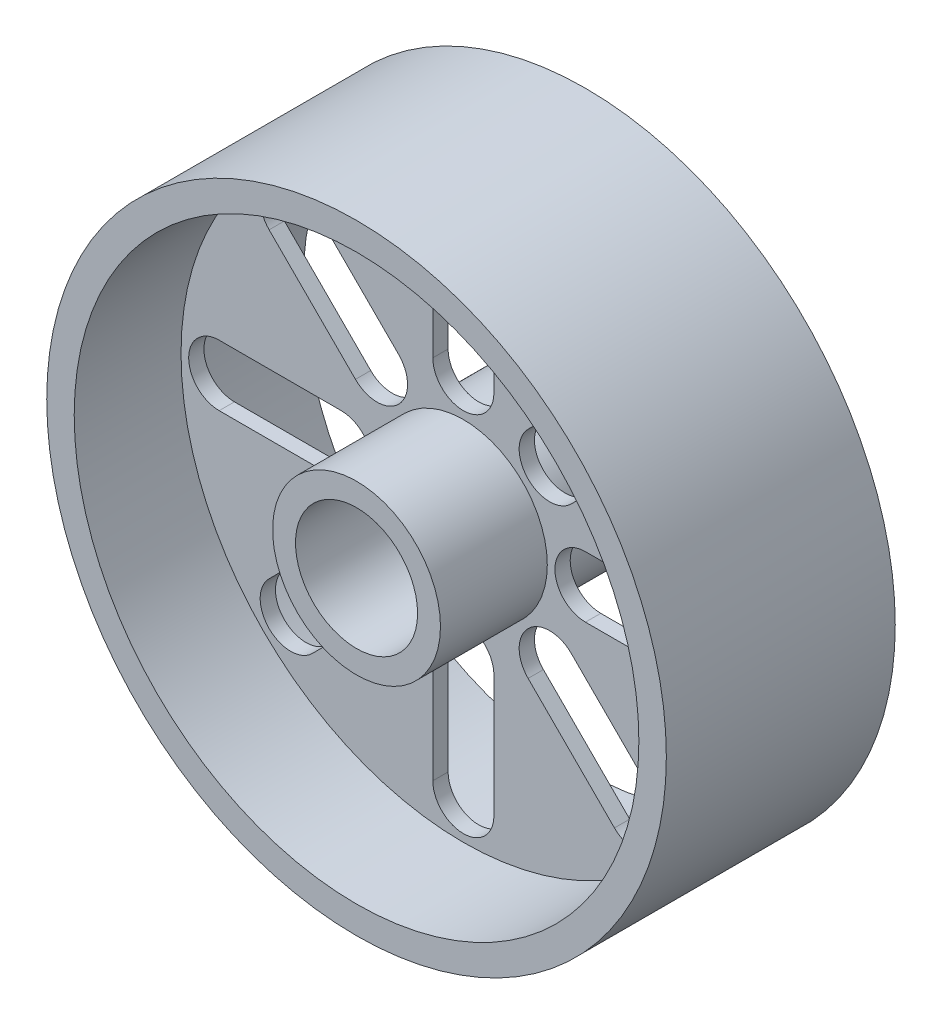
SolidWorks part; units mm, degrees
ref_plane "Front Plane" through (0, 0, 0) normal (0, 0, 1) x (1, 0, 0)
ref_plane "Top Plane" through (0, 0, 0) normal (0, 1, 0) x (1, 0, 0)
ref_plane "Right Plane" through (0, 0, 0) normal (1, 0, 0) x (0, 0, -1)
sketch "Sketch1" plane through (0, 0, 0) normal (0, 0, 1) x (1, 0, 0)
  line L0 (0, 80) -> (0, 40) construction
  line L1 (0, -55) -> (0, 55) construction
  line L2 (10, 80) -> (10, 40)
  line L3 (-10, 80) -> (-10, 40)
  line L4 (56.5685, 56.5685) -> (28.2843, 28.2843) construction
  line L5 (63.6396, 49.4975) -> (35.3553, 21.2132)
  line L6 (49.4975, 63.6396) -> (21.2132, 35.3553)
  line L7 (80, 0) -> (40, 0) construction
  line L8 (80, -10) -> (40, -10)
  line L9 (80, 10) -> (40, 10)
  line L10 (56.5685, -56.5685) -> (28.2843, -28.2843) construction
  line L11 (49.4975, -63.6396) -> (21.2132, -35.3553)
  line L12 (63.6396, -49.4975) -> (35.3553, -21.2132)
  line L13 (0, -80) -> (0, -40) construction
  line L14 (-10, -80) -> (-10, -40)
  line L15 (10, -80) -> (10, -40)
  line L16 (-56.5685, -56.5685) -> (-28.2843, -28.2843) construction
  line L17 (-63.6396, -49.4975) -> (-35.3553, -21.2132)
  line L18 (-49.4975, -63.6396) -> (-21.2132, -35.3553)
  line L19 (-80, 0) -> (-40, 0) construction
  line L20 (-80, 10) -> (-40, 10)
  line L21 (-80, -10) -> (-40, -10)
  line L22 (-56.5685, 56.5685) -> (-28.2843, 28.2843) construction
  line L23 (-49.4975, 63.6396) -> (-21.2132, 35.3553)
  line L24 (-63.6396, 49.4975) -> (-35.3553, 21.2132)
  circle A0 centre (0, 0) radius 101.5
  circle A1 centre (0, 0) radius 20
  arc A2 (10, 80) -> (-10, 80) centre (0, 80) ccw
  arc A3 (-10, 40) -> (10, 40) centre (0, 40) ccw
  arc A4 (63.6396, 49.4975) -> (49.4975, 63.6396) centre (56.5685, 56.5685) ccw
  arc A5 (21.2132, 35.3553) -> (35.3553, 21.2132) centre (28.2843, 28.2843) ccw
  arc A6 (80, -10) -> (80, 10) centre (80, 0) ccw
  arc A7 (40, 10) -> (40, -10) centre (40, 0) ccw
  arc A8 (49.4975, -63.6396) -> (63.6396, -49.4975) centre (56.5685, -56.5685) ccw
  arc A9 (35.3553, -21.2132) -> (21.2132, -35.3553) centre (28.2843, -28.2843) ccw
  arc A10 (-10, -80) -> (10, -80) centre (0, -80) ccw
  arc A11 (10, -40) -> (-10, -40) centre (0, -40) ccw
  arc A12 (-63.6396, -49.4975) -> (-49.4975, -63.6396) centre (-56.5685, -56.5685) ccw
  arc A13 (-21.2132, -35.3553) -> (-35.3553, -21.2132) centre (-28.2843, -28.2843) ccw
  arc A14 (-80, 10) -> (-80, -10) centre (-80, 0) ccw
  arc A15 (-40, -10) -> (-40, 10) centre (-40, 0) ccw
  arc A16 (-49.4975, 63.6396) -> (-63.6396, 49.4975) centre (-56.5685, 56.5685) ccw
  arc A17 (-35.3553, 21.2132) -> (-21.2132, 35.3553) centre (-28.2843, 28.2843) ccw
  point P8 (0, 60)
  point P18 (42.4264, 42.4264)
  point P25 (60, 0)
  point P32 (42.4264, -42.4264)
  point P39 (0, -60)
  point P46 (-42.4264, -42.4264)
  point P53 (-60, 0)
  point P60 (-42.4264, 42.4264)
  point P65 (0, 0)
  dimension "D1" = 203
  dimension "D2" = 40
  dimension "D3" = 60
  dimension "D4" = 40
  dimension "D5" = 20
  dimension "D6" = 8
extrude "Boss-Extrude1" add sketch "Sketch1" along normal blind 75
sketch "Sketch2" plane through (0, 0, 75) normal (0, 0, 1) x (1, 0, 0)
  circle A0 centre (0, 0) radius 27.5
  circle A1 centre (0, 0) radius 92.5
  dimension "D1" = 55
  dimension "D2" = 185
extrude "Cut-Extrude1" cut sketch "Sketch2" against normal blind 35
sketch "Sketch3" plane through (0, 0, 0) normal (0, 0, -1) x (-1, 0, 0)
  circle A1 centre (0, 0) radius 92.5
  circle A2 centre (0, 0) radius 92.5
  circle A3 centre (0, 0) radius 27.5
  circle A4 centre (0, 0) radius 27.5
  dimension "D1" = 0
  dimension "D2" = 0
extrude "Cut-Extrude2" cut sketch "Sketch3" against normal blind 35
